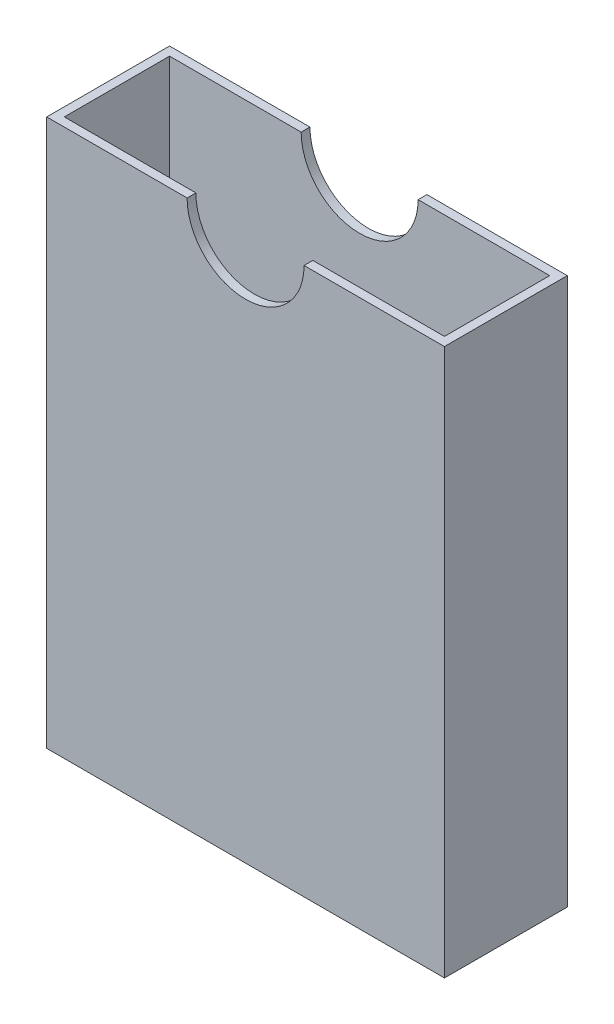
SolidWorks part; units mm, degrees
ref_plane "Front Plane" through (0, 0, 0) normal (0, 0, 1) x (1, 0, 0)
ref_plane "Top Plane" through (0, 0, 0) normal (0, 1, 0) x (1, 0, 0)
ref_plane "Right Plane" through (0, 0, 0) normal (1, 0, 0) x (0, 0, -1)
sketch "Sketch1" plane through (0, 0, 0) normal (0, 1, 0) x (1, 0, 0)
  line L0 (32.5, -9) -> (32.5, -10.5) construction
  line L1 (-32.5, 9) -> (32.5, 9)
  line L2 (-32.5, 9) -> (-32.5, -9)
  line L3 (-32.5, -9) -> (32.5, -9)
  line L4 (32.5, 9) -> (32.5, -9)
  line L5 (-32.5, 9) -> (32.5, -9) construction
  line L6 (-32.5, -9) -> (32.5, 9) construction
  line L7 (-34, 10.5) -> (34, 10.5)
  line L8 (-34, 10.5) -> (-34, -10.5)
  line L9 (-34, -10.5) -> (34, -10.5)
  line L10 (34, 10.5) -> (34, -10.5)
  line L11 (-34, 10.5) -> (34, -10.5) construction
  line L12 (-34, -10.5) -> (34, 10.5) construction
  line L13 (32.5, -9) -> (34, -9) construction
  point P0 (0, 0)
  point P6 (0, 0)
  dimension "D1" = 65
  dimension "D2" = 1.5
  dimension "D3" = 18
extrude "Boss-Extrude1" add sketch "Sketch1" along normal blind 1.5 contours L4 L1 L2 L3 | L10 L7 L8 L9 L1 L4 L3 L2
sketch "Sketch2" plane through (0, 1.5, 0) normal (0, 1, 0) x (1, 0, 0)
  line L4 (34, 10.5) -> (-34, 10.5)
  line L5 (34, -10.5) -> (34, 10.5)
  line L6 (-34, -10.5) -> (34, -10.5)
  line L7 (-34, 10.5) -> (-34, -10.5)
  line L8 (34, 10.5) -> (-34, 10.5)
  line L9 (34, -10.5) -> (34, 10.5)
  line L10 (-34, -10.5) -> (34, -10.5)
  line L11 (-34, 10.5) -> (-34, -10.5)
  line L12 (32.5, 9) -> (-32.5, 9)
  line L13 (32.5, -9) -> (32.5, 9)
  line L14 (-32.5, -9) -> (32.5, -9)
  line L15 (-32.5, 9) -> (-32.5, -9)
  line L16 (32.5, 9) -> (-32.5, 9)
  line L17 (32.5, -9) -> (32.5, 9)
  line L18 (-32.5, -9) -> (32.5, -9)
  line L19 (-32.5, 9) -> (-32.5, -9)
  dimension "D1" = 0
  dimension "D2" = 0
extrude "Boss-Extrude2" add sketch "Sketch2" along normal blind 92
sketch "Sketch3" plane through (0, 0, 10.5) normal (0, 0, 1) x (1, 0, 0)
  line L0 (-34, 93.5) -> (34, 93.5) construction
  line L1 (0, 93.5) -> (0, 0) construction
  circle A0 centre (0, 93.5) radius 10
  circle A1 centre (0, 93.5) radius 13
  circle A2 centre (0, 47.6141) radius 5.8557
  line M3 (34, 93.5) -> (-34, 93.5)
  dimension "D1" = 20
  dimension "D3" = 26
extrude "Cut-Extrude1" cut sketch "Sketch3" against normal up to surface (21 mm away) contours L1 A0 M3 | L1 A0 M3 up to face at (0, 46.75, -10.5)
